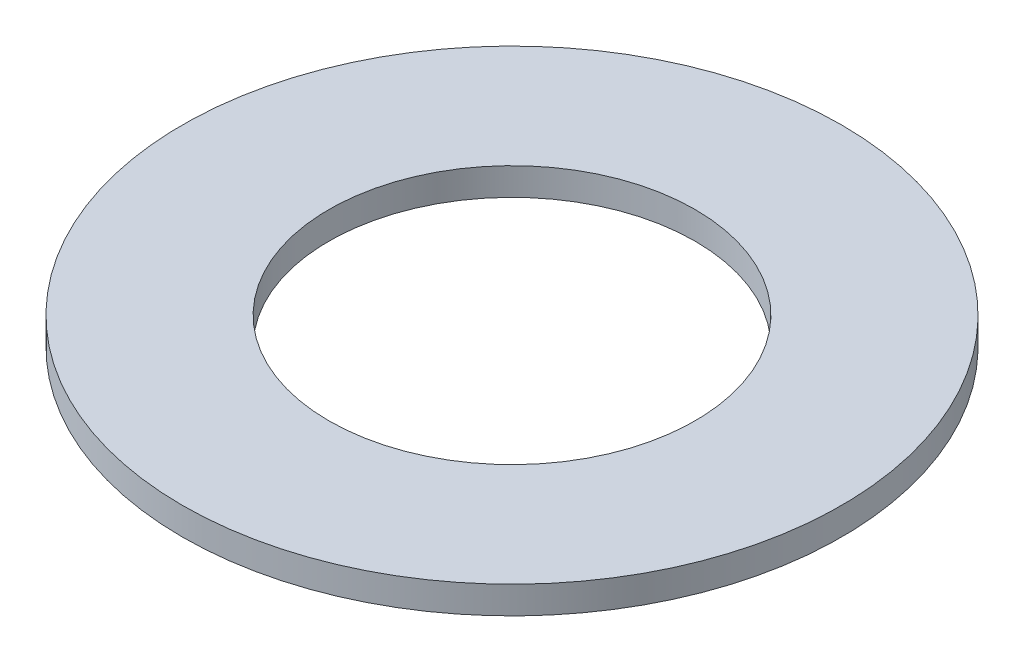
SolidWorks part; units mm, degrees
ref_plane "Front Plane" through (0, 0, 0) normal (0, 0, 1) x (1, 0, 0)
ref_plane "Top Plane" through (0, 0, 0) normal (0, 1, 0) x (1, 0, 0)
ref_plane "Right Plane" through (0, 0, 0) normal (1, 0, 0) x (0, 0, -1)
sketch "Sketch1" plane through (0, 0, 0) normal (0, 1, 0) x (1, 0, 0)
  circle A0 centre (0, 0) radius 36
  circle A1 centre (0, 0) radius 20
  dimension "D1" = 72
  dimension "D2" = 40
extrude "Boss-Extrude1" add sketch "Sketch1" along normal blind 3
